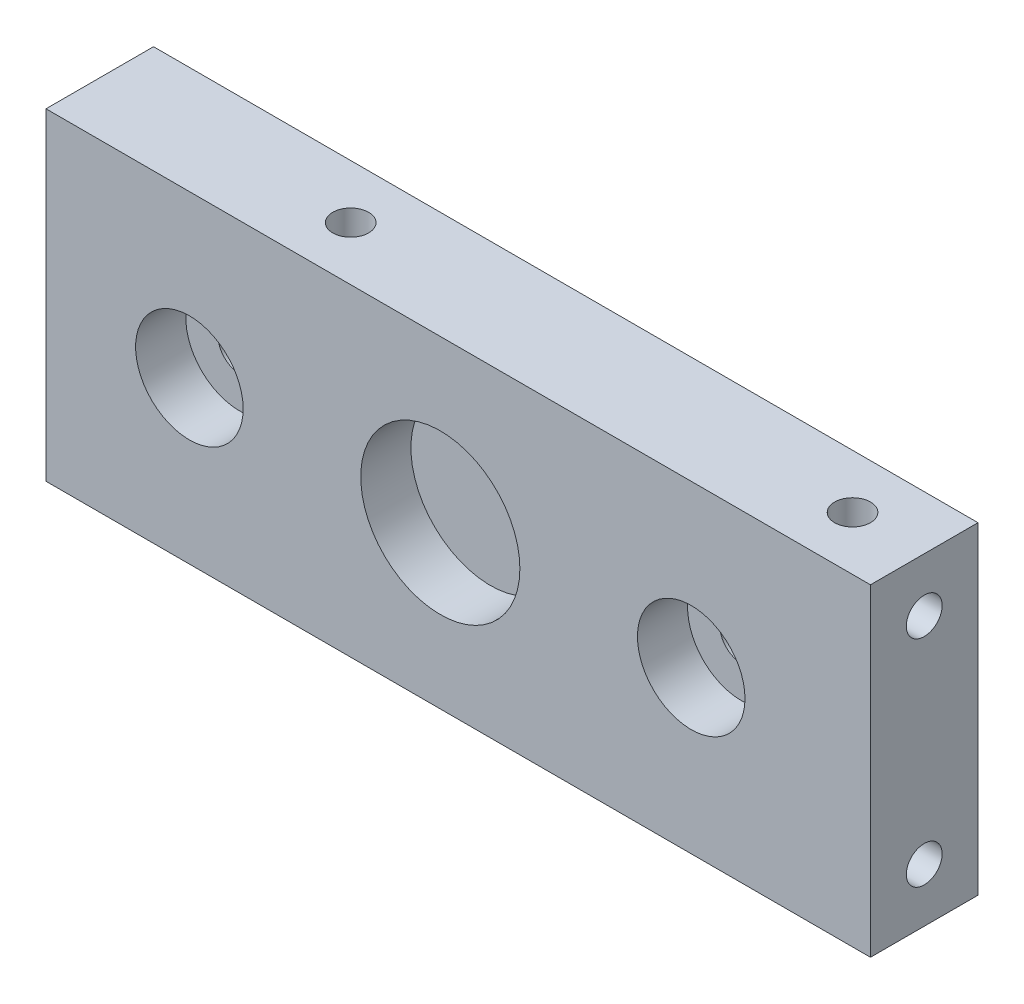
SolidWorks part; units mm, degrees
ref_plane "Front Plane" through (0, 0, 0) normal (0, 0, 1) x (1, 0, 0)
ref_plane "Top Plane" through (0, 0, 0) normal (0, 1, 0) x (1, 0, 0)
ref_plane "Right Plane" through (0, 0, 0) normal (1, 0, 0) x (0, 0, -1)
sketch "Sketch1" plane through (0, 0, 0) normal (0, 0, 1) x (1, 0, 0)
  line L0 (-50, 0) -> (50, 0) construction
  line L1 (50, -22.5) -> (-50, -22.5)
  line L2 (50, -22.5) -> (50, 22.5)
  line L3 (50, 22.5) -> (-50, 22.5)
  line L4 (-50, -22.5) -> (-50, 22.5)
  line L5 (50, -22.5) -> (-50, 22.5) construction
  line L6 (50, 22.5) -> (-50, -22.5) construction
  line L7 (0, 22.5) -> (0, 0) construction
  circle A1 centre (-35, 0) radius 3
  circle A2 centre (35, 0) radius 3
  point P0 (0, 0)
  dimension "D3" = 6
  dimension "D1" = 100
  dimension "D2" = 45
  dimension "D5" = 15
extrude "Boss-Extrude1" add sketch "Sketch1" along normal blind 15
sketch "Sketch2" plane through (0, 0, 15) normal (0, 0, 1) x (1, 0, 0)
  circle A0 centre (-35, 0) radius 7.5
  circle A1 centre (35, 0) radius 7.5
  circle A2 centre (0, 0) radius 11.1
  dimension "D1" = 15
  dimension "D2" = 15
  dimension "D3" = 22.2
extrude "Cut-Extrude1" cut sketch "Sketch2" against normal blind 7
sketch "Sketch4" plane through (50, 0, 0) normal (1, 0, 0) x (0, 0, -1)
  line L1 (-15, 22.5) -> (0, 22.5)
  line L2 (-15, 22.5) -> (-15, -22.5)
  line L3 (-15, -22.5) -> (0, -22.5)
  line L4 (0, 22.5) -> (0, -22.5)
extrude "Boss-Extrude2" add sketch "Sketch4" along normal blind 10
sketch "Sketch5" plane through (0, 0, 0) normal (0, 0, -1) x (-1, 0, 0)
  circle A0 centre (-35, 0) radius 5.5
  circle A1 centre (35, 0) radius 5.5
  dimension "D1" = 11
  dimension "D2" = 11
extrude "Cut-Extrude2" cut sketch "Sketch5" against normal blind 5
sketch "Sketch7" plane through (-50, 0, 0) normal (-1, 0, 0) x (0, 0, 1)
  line L0 (7.5, 22.5) -> (7.5, -22.5) construction
  line L1 (15, 22.5) -> (0, 22.5) construction
  line L2 (15, -22.5) -> (0, -22.5) construction
  circle A0 centre (7.5, 15) radius 2.5
  circle A1 centre (7.5, -15) radius 2.5
  dimension "D2" = 5
  dimension "D1" = 7.5
  dimension "D3" = 7.5
extrude "Cut-Extrude4" cut sketch "Sketch7" against normal blind 10
sketch "Sketch9" plane through (0, 22.5, 0) normal (0, 1, 0) x (1, 0, 0)
  line L0 (-50, -7.5) -> (60, -7.5) construction
  line L1 (-50, -15) -> (-50, 0) construction
  line L2 (60, 0) -> (60, -15) construction
  circle A0 centre (-20, -7.5) radius 2.5
  circle A1 centre (50, -7.5) radius 2.5
  dimension "D3" = 5
  dimension "D4" = 5
  dimension "D1" = 10
  dimension "D2" = 80
extrude "Cut-Extrude6" cut sketch "Sketch9" against normal blind 10
ref_plane "Plane1" through (5, 0, 0) normal (1, 0, 0) x (0, 0, -1)
mirror "Mirror1" about plane through (5, 0, 0) normal (1, 0, 0) of "Cut-Extrude4"
sketch "Sketch11" plane through (-50, 0, 0) normal (-1, 0, 0) x (0, 0, 1)
  line L0 (15, 22.5) -> (0, 22.5) construction
  line L1 (0, 22.5) -> (15, 22.5)
  line L2 (0, 22.5) -> (0, -22.5)
  line L3 (0, -22.5) -> (15, -22.5)
  line L4 (15, 22.5) -> (15, -22.5)
  line L5 (0, 22.5) -> (0, -22.5) construction
  circle A0 centre (7.5, -15) radius 2.5
  circle A1 centre (7.5, 15) radius 2.5
extrude "Boss-Extrude4" add sketch "Sketch11" along normal blind 5
